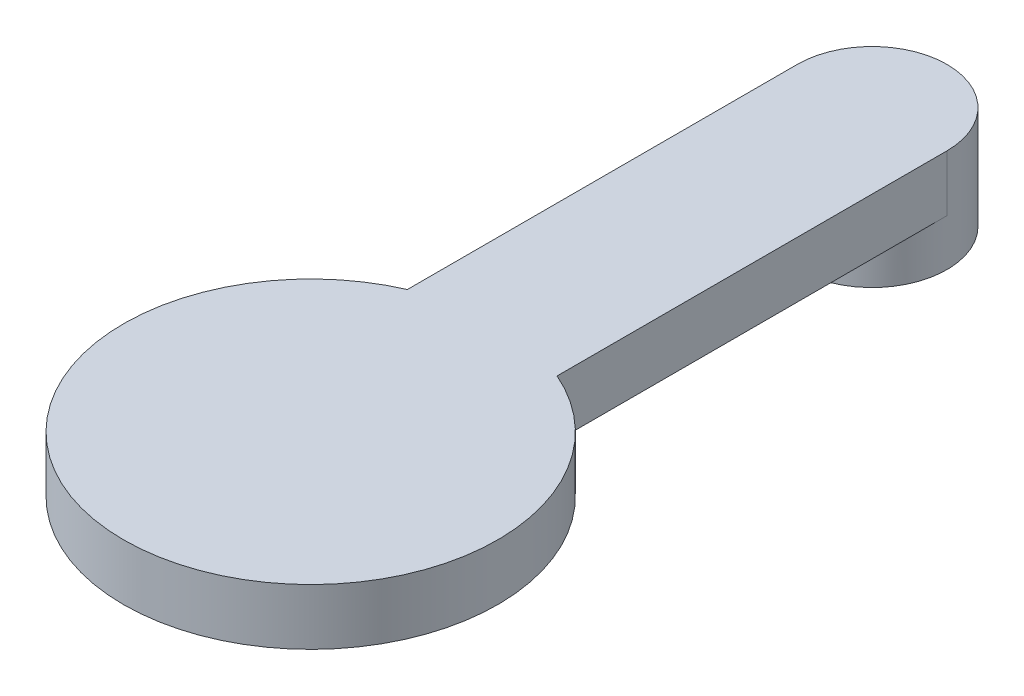
SolidWorks part; units mm, degrees
ref_plane "前视基准面" through (0, 0, 0) normal (0, 0, 1) x (1, 0, 0)
ref_plane "上视基准面" through (0, 0, 0) normal (0, 1, 0) x (1, 0, 0)
ref_plane "右视基准面" through (0, 0, 0) normal (1, 0, 0) x (0, 0, -1)
other "Configuration Table"
sketch "草图1" plane through (0, 0, 0) normal (0, 1, 0) x (1, 0, 0)
  line L1 (0, 3.0022) -> (-2.6, 1.5011)
  line L2 (-2.6, 1.5011) -> (-2.6, -1.5011)
  line L3 (-2.6, -1.5011) -> (0, -3.0022)
  line L4 (0, -3.0022) -> (2.6, -1.5011)
  line L5 (2.6, -1.5011) -> (2.6, 1.5011)
  line L6 (2.6, 1.5011) -> (0, 3.0022)
  circle A0 centre (0, 0) radius 2.6 construction
  circle A1 centre (0, 0) radius 4
  dimension "D1" = 5.2
  dimension "D2" = 8
extrude "凸台-拉伸1" add sketch "草图1" along normal blind 2.5
sketch "草图2" plane through (0, 2.5, 0) normal (0, 1, 0) x (1, 0, 0)
  line L0 (4, 0) -> (4, -20.8348)
  line L1 (-4, -20.8348) -> (-4, 0)
  arc A1 (4, 0) -> (-4, 0) centre (0, 0) ccw
  arc A2 (-4, -20.8348) -> (4, -20.8348) centre (0, -30) ccw
  dimension "D2" = 20
  dimension "D3" = 8
  dimension "D1" = 30
extrude "凸台-拉伸2" add sketch "草图2" along normal blind 3
